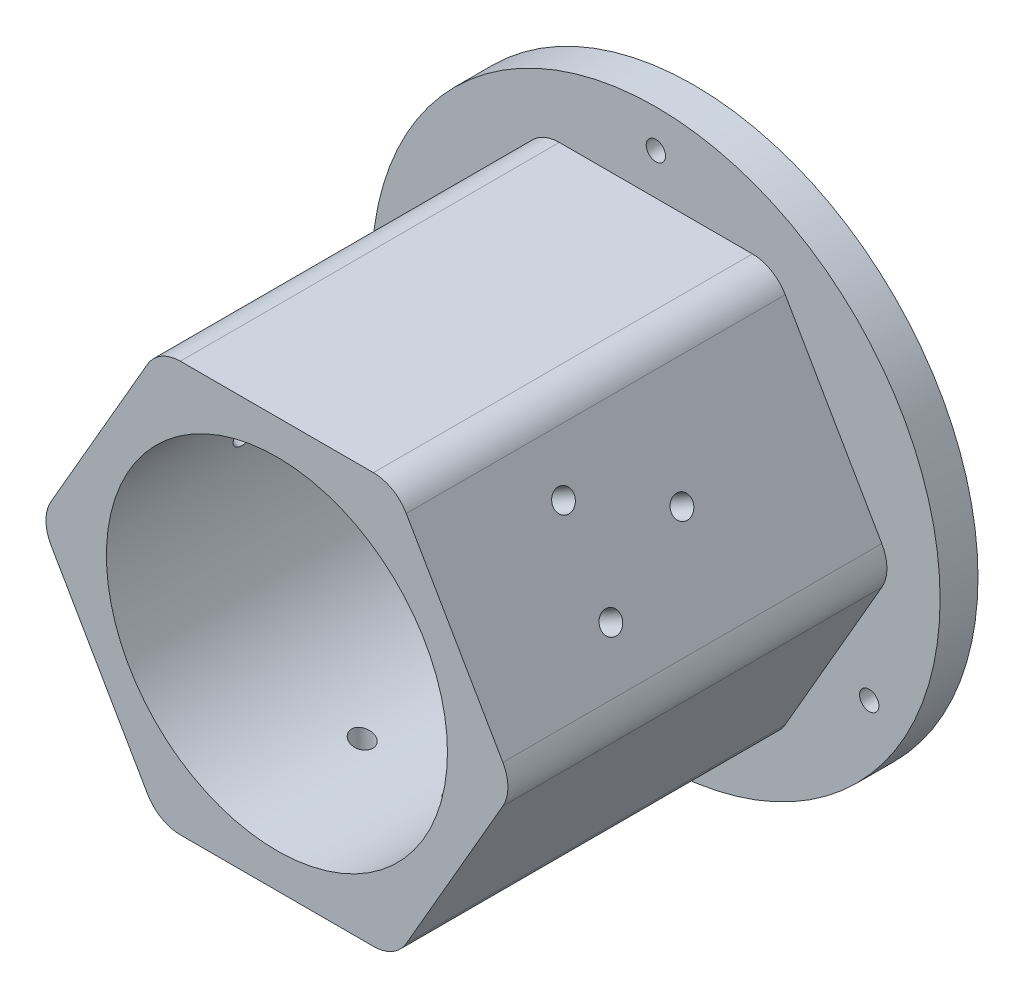
SolidWorks part; units mm, degrees
material "ABS PC"
ref_plane "Front Plane" through (0, 0, 0) normal (0, 0, 1) x (1, 0, 0)
ref_plane "Top Plane" through (0, 0, 0) normal (0, 1, 0) x (1, 0, 0)
ref_plane "Right Plane" through (0, 0, 0) normal (1, 0, 0) x (0, 0, -1)
sketch "Sketch1" plane through (0, 0, 0) normal (0, 0, 1) x (1, 0, 0)
  circle A0 centre (0, 0) radius 75
  dimension "D1" = 150
extrude "Boss-Extrude1" add sketch "Sketch1" along normal blind 10
sketch "Sketch2" plane through (0, 0, 10) normal (0, 0, 1) x (1, 0, 0)
  line L1 (59.6132, 5) -> (34.1368, 49.1266)
  line L2 (25.4765, 54.1266) -> (-25.4765, 54.1266)
  line L3 (-34.1368, 49.1266) -> (-59.6132, 5)
  line L4 (-59.6132, -5) -> (-34.1368, -49.1266)
  line L5 (-25.4765, -54.1266) -> (25.4765, -54.1266)
  line L6 (34.1368, -49.1266) -> (59.6132, -5)
  circle A0 centre (0, 0) radius 62.5 construction
  arc A1 (25.4765, -54.1266) -> (34.1368, -49.1266) centre (25.4765, -44.1266) ccw
  arc A2 (-34.1368, -49.1266) -> (-25.4765, -54.1266) centre (-25.4765, -44.1266) ccw
  arc A3 (-59.6132, -5) -> (-59.6132, 5) centre (-50.953, 0) cw
  arc A4 (-25.4765, 54.1266) -> (-34.1368, 49.1266) centre (-25.4765, 44.1266) ccw
  arc A5 (34.1368, 49.1266) -> (25.4765, 54.1266) centre (25.4765, 44.1266) ccw
  arc A6 (59.6132, -5) -> (59.6132, 5) centre (50.953, 0) ccw
  point P11 (31.25, -54.1266)
  dimension "D1" = 10
  dimension "D2" = 10
extrude "Boss-Extrude2" add sketch "Sketch2" along normal blind 100
sketch "Sketch4" plane through (0, 0, 110) normal (0, 0, 1) x (1, 0, 0)
  circle A0 centre (0, 0) radius 45
extrude "Cut-Extrude1" cut sketch "Sketch4" against normal up to surface (100 mm away) up to face at (0, 0, 10)
sketch "Sketch5" plane through (0, -54.1266, 0) normal (0, -1, 0) x (1, 0, 0)
  circle A0 centre (0, 50) radius 2.8
  circle A1 centre (-12.5, 75) radius 2.8
  circle A2 centre (12.5, 75) radius 2.8
  dimension "D1" = 25
  dimension "D5" = 5.6
  dimension "D6" = 5.6
  dimension "D7" = 5.6
  dimension "D2" = 25
  dimension "D3" = 12.5
  dimension "D4" = 0
  dimension "D8" = 50
  dimension "D9" = 12.5
extrude "Cut-Extrude2" cut sketch "Sketch5" against normal up to surface (9.2138 mm away)
pattern_circular "CirPattern1" count 3 every 120 about axis through (0, 0, -117.2792) along (0, 0, 1) of "Cut-Extrude2"
sketch "Sketch7" plane through (0, 0, 10) normal (0, 0, 1) x (1, 0, 0)
  circle A0 centre (0, 65) radius 2.55
  circle A1 centre (56.2917, -32.5) radius 2.55
  circle A2 centre (-56.2917, -32.5) radius 2.55
  point P9 (0, 0)
  dimension "D1" = 65
  dimension "D4" = 5.1
  dimension "D2" = 0
  dimension "D3" = 3
extrude "Cut-Extrude3" cut sketch "Sketch7" against normal up to surface (10 mm away) up to face at (75, 0, 0)
